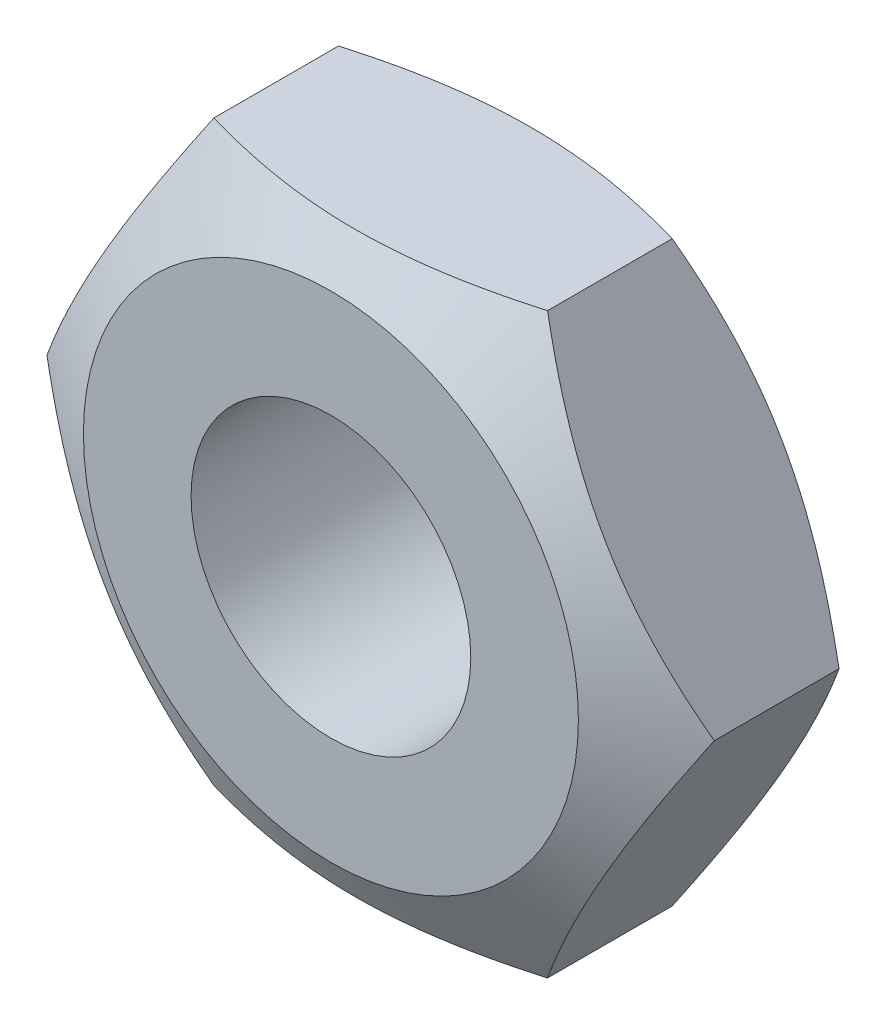
SolidWorks part; units mm, degrees
ref_plane "Front Plane" through (0, 0, 0) normal (0, 0, 1) x (1, 0, 0)
ref_plane "Top Plane" through (0, 0, 0) normal (0, 1, 0) x (1, 0, 0)
ref_plane "Right Plane" through (0, 0, 0) normal (1, 0, 0) x (0, 0, -1)
sketch "Sketch1" plane through (0, 0, 0) normal (0, 0, 1) x (1, 0, 0)
  line L2 (4.1216, 7.1374) -> (-4.1204, 7.1381)
  line L3 (-4.1204, 7.1381) -> (-8.242, 0.0007)
  line L4 (-8.242, 0.0007) -> (-4.1216, -7.1374)
  line L5 (-4.1216, -7.1374) -> (4.1204, -7.1381)
  line L6 (4.1204, -7.1381) -> (8.242, -0.0007)
  line L7 (8.242, -0.0007) -> (4.1216, 7.1374)
  circle A0 centre (0, 0) radius 4.7625
extrude "Boss-Extrude1" add sketch "Sketch1" along normal blind 5.5372 contours L3 L4 L5 L6 L7 L2
sketch "Sketch6" plane through (0, 0, 0) normal (0, 0, -1) x (-1, 0, 0)
  circle A0 centre (0, 0) radius 6.1127
extrude "Cut-Extrude4" cut sketch "Sketch6" along direction (0, 0, 1) on the side against the normal through all draft 60 flip side to cut
ref_plane "Plane2" through (0, 0, 2.7686) normal (0, 0, 1) x (1, 0, 0)
mirror "Mirror1" about plane through (0, 0, 2.7686) normal (0, 0, 1) of "Cut-Extrude4"
hole_wizard "5/16-24 Tapped Hole2" positions "Sketch11" profile "Sketch10" tap size "5/16-24" standard "ANSI Inch"
sketch "Sketch11" plane through (0, 0, 5.5372) normal (0, 0, 1) x (1, 0, 0)
  point P0 (0, 0)
sketch "Sketch10" plane through (0, 0, 5.5372) normal (1, 0, 0) x (0, -1, 0)
  line L0 (0, 0) -> (0, 23.4116)
  line L1 (0, 23.4116) -> (3.4544, 21.336)
  line L2 (3.4544, 21.336) -> (3.4544, 0)
  line L5 (3.4544, 0) -> (0, 0)
  line L10 (0, 23.4116) -> (-3.4544, 21.336) construction
  line L11 (0, -6.35) -> (0, 107.95) construction
  dimension "Tap Drill Dia." = 6.9088
  dimension "Tap Drill Depth" = 21.336
  dimension "Drill Angle" = 118
cosmetic thread "Hole Thread2" parameters "D1"=5.5372, "D2"=7.9375
